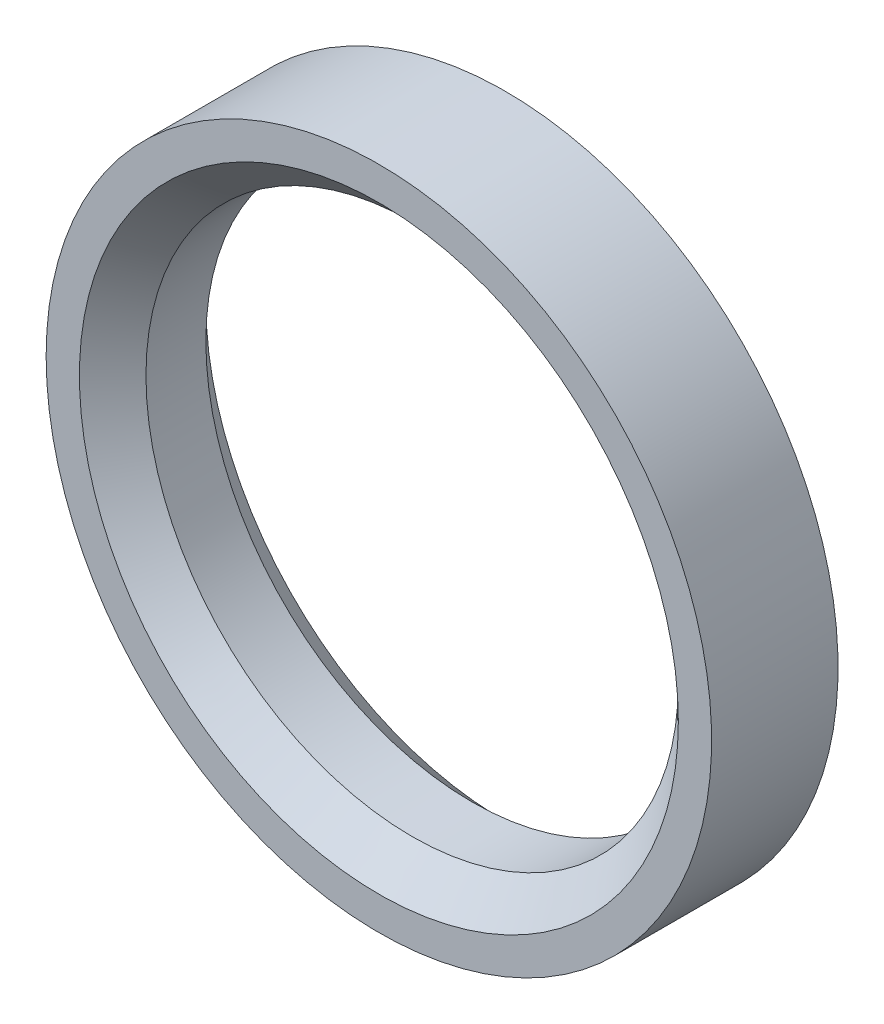
SolidWorks part; units mm, degrees
ref_plane "前基準面" through (0, 0, 0) normal (0, 0, 1) x (1, 0, 0)
ref_plane "上基準面" through (0, 0, 0) normal (0, 1, 0) x (1, 0, 0)
ref_plane "右基準面" through (0, 0, 0) normal (1, 0, 0) x (0, 0, -1)
sketch "草圖1" plane through (0, 0, 0) normal (0, 0, 1) x (1, 0, 0)
  circle A0 centre (0, 0) radius 5
  circle A1 centre (0, 0) radius 4
  dimension "D1" = 10
  dimension "D2" = 8
extrude "伸長1" add sketch "草圖1" along normal blind 1.9
chamfer "導角1" distance 0.5 angle 45 2 edges at (4, 0, 0) (4, 0, 1.9)
